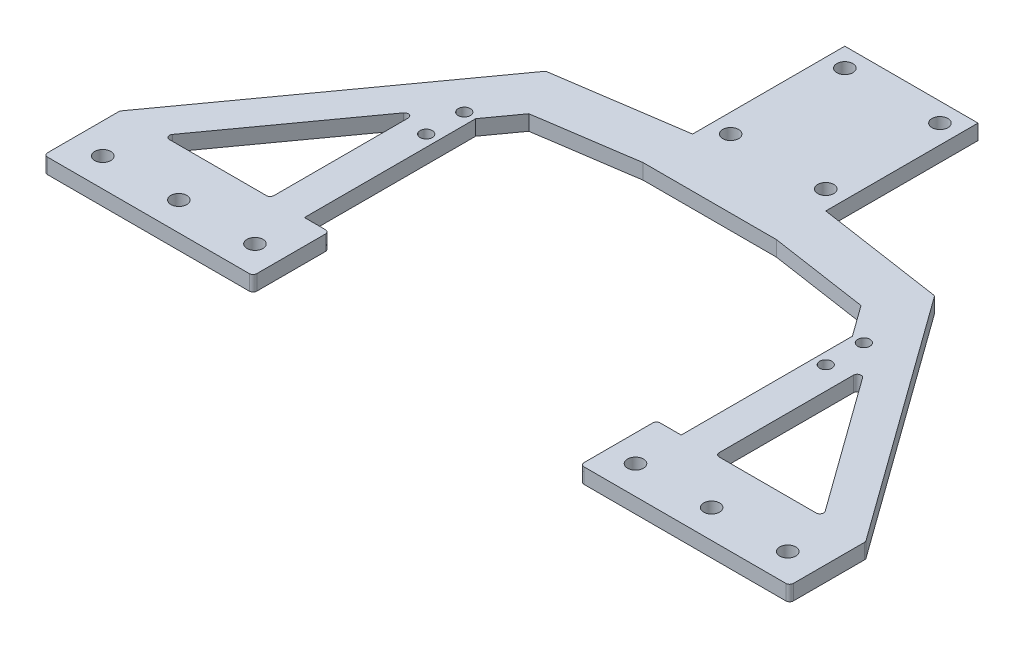
SolidWorks part; units mm, degrees
material "Thornel Mat VMA"
ref_plane "前视基准面" through (0, 0, 0) normal (0, 0, 1) x (1, 0, 0)
ref_plane "上视基准面" through (0, 0, 0) normal (0, 1, 0) x (1, 0, 0)
ref_plane "右视基准面" through (0, 0, 0) normal (1, 0, 0) x (0, 0, -1)
sketch "草图1" plane through (0, 0, 0) normal (0, 1, 0) x (1, 0, 0)
  line L0 (0, 0) -> (0, -110)
  line L1 (0, -110) -> (-62.5, -110)
  line L2 (-62.5, -110) -> (-62.5, -130)
  line L3 (-62.5, -130) -> (97.5, -130)
  line L4 (97.5, -130) -> (97.5, -110)
  line L5 (97.5, -110) -> (35, -110)
  line L6 (35, -110) -> (35, 0)
  line L7 (35, 0) -> (0, 0)
  line L9 (5, -5) -> (30, -5) construction
  line L10 (5, -5) -> (5, -35) construction
  line L11 (5, -35) -> (30, -35) construction
  line L12 (30, -5) -> (30, -35) construction
  circle A0 centre (5, -5) radius 2.1
  circle A1 centre (30, -5) radius 2.1
  circle A2 centre (5, -35) radius 2.1
  circle A3 centre (30, -35) radius 2.1
  circle A4 centre (-52.5, -122.5) radius 2.1
  circle A5 centre (-32.5, -122.5) radius 2.1
  circle A6 centre (-12.5, -122.5) radius 2.1
  circle A7 centre (7.5, -122.5) radius 2.1
  circle A8 centre (27.5, -122.5) radius 2.1
  circle A9 centre (47.5, -122.5) radius 2.1
  circle A10 centre (67.5, -122.5) radius 2.1
  circle A11 centre (87.5, -122.5) radius 2.1
  point P7 (17.5, -5)
  dimension "D10" = 4.2
  dimension "D11" = 7.5
  dimension "D13" = 4.2
  dimension "D1" = 35
  dimension "D2" = 130
  dimension "D3" = 20
  dimension "D4" = 160
  dimension "D5" = 62.5
  dimension "D6" = 5
  dimension "D7" = 5
  dimension "D8" = 5
  dimension "D9" = 30
  dimension "D12" = 10
  dimension "D15" = 10
  dimension "D14" = 8
extrude "凸台-拉伸1" add sketch "草图1" along normal blind 4
sketch "草图2" plane through (0, 4, 0) normal (0, 1, 0) x (1, 0, 0)
  line L0 (17.5, 0) -> (17.5, -130) construction
  line L1 (-35, -65) -> (70, -65) construction
  line L2 (-35, -65) -> (-35, -75) construction
  line L3 (-35, -75) -> (70, -75) construction
  line L5 (35, 0) -> (0, 0) construction
  line L6 (-62.5, -130) -> (97.5, -130) construction
  line L7 (70, -65) -> (70, -75) construction
  line L34 (0, 0) -> (0, -110) construction
  line L35 (0, -40) -> (0, -53)
  line L44 (0, -40) -> (-33.6, -45)
  line L45 (-33.6, -45) -> (-80.5, -110)
  line L46 (0, -53) -> (-26.1492, -56.8913)
  line L47 (-26.1492, -56.8913) -> (-32, -65)
  line L48 (-32, -65) -> (-32, -110)
  line L50 (-80.5, -110) -> (-80.5, -130)
  line L51 (-80.5, -130) -> (-62.5, -130)
  line L52 (-62.5, -130) -> (-62.5, -110)
  line L65 (0, -110) -> (-62.5, -110) construction
  line L66 (-32, -110) -> (-41, -110)
  line L67 (-69.4018, -110) -> (-41, -70.6372)
  line L68 (-41, -70.6372) -> (-41, -110)
  line L69 (-62.5, -110) -> (-69.4018, -110)
  line L71 (67, -65) -> (67, -110)
  line L72 (61.1492, -56.8913) -> (67, -65)
  line L73 (35, -53) -> (61.1492, -56.8913)
  line L74 (35, -40) -> (35, -53)
  line L75 (35, -40) -> (68.6, -45)
  line L76 (68.6, -45) -> (115.5, -110)
  line L77 (115.5, -110) -> (115.5, -130)
  line L78 (115.5, -130) -> (97.5, -130)
  line L79 (97.5, -130) -> (97.5, -110)
  line L80 (97.5, -110) -> (104.4018, -110)
  line L81 (104.4018, -110) -> (76, -70.6372)
  line L82 (76, -70.6372) -> (76, -110)
  line L83 (67, -110) -> (76, -110)
  line L84 (-52.5, -122.5) -> (-72.5, -122.5) construction
  circle A0 centre (-35, -65) radius 1.6
  circle A1 centre (-35, -75) radius 1.6
  circle A2 centre (70, -65) radius 1.6
  circle A3 centre (70, -75) radius 1.6
  circle A4 centre (-52.5, -122.5) radius 2.1 construction
  circle A5 centre (-72.5, -122.5) radius 2.1
  circle A6 centre (107.5, -122.5) radius 2.1
  dimension "D3" = 3.2
  dimension "D15" = 20
  dimension "D1" = 105
  dimension "D2" = 10
  dimension "D4" = 3
  dimension "D5" = 40
  dimension "D6" = 55
  dimension "D7" = 9
  dimension "D8" = 13
  dimension "D9" = 13
  dimension "D10" = 5
  dimension "D11" = 18
  dimension "D12" = 9
extrude "凸台-拉伸2" add sketch "草图2" against normal up to surface (4 mm away) up to face at (17.5, 0, 87.5)
sketch "草图3" plane through (0, 4, 0) normal (0, 1, 0) x (1, 0, 0)
  line L0 (0, -53) -> (35, -53)
  line L4 (35, -53) -> (35, -110)
  line L5 (35, -110) -> (60.5, -110)
  line L7 (60.5, -110) -> (60.5, -130)
  line L8 (-80.5, -130) -> (115.5, -130) construction
  line L9 (60.5, -130) -> (-25.5, -130)
  line L10 (-25.5, -130) -> (-25.5, -110)
  line L12 (-25.5, -110) -> (0, -110)
  line L13 (0, -110) -> (0, -53)
  line L15 (-80.5, -130) -> (115.5, -130) construction
  line L17 (0, -110) -> (-32, -110) construction
  line L18 (67, -110) -> (35, -110) construction
  circle A2 centre (-32.5, -122.5) radius 2.1 construction
  circle A3 centre (67.5, -122.5) radius 2.1 construction
  dimension "D1" = 7
  dimension "D2" = 7
extrude "切除-拉伸1" cut sketch "草图3" against normal through all
fillet "圆角2" radius 1 6 edges at (104.4018, 2, 110) (76, 2, 110) (76, 2, 70.6372) (-41, 2, 110) (-69.4018, 2, 110) (-41, 2, 70.6372)
fillet "圆角3" radius 1 10 edges at (115.5, 2, 130) (115.5, 2, 110) (68.6, 2, 45) (60.5, 2, 110) (60.5, 2, 130) (-25.5, 2, 130) (-25.5, 2, 110) (-33.6, 2, 45) (-80.5, 2, 110) (-80.5, 2, 130)
